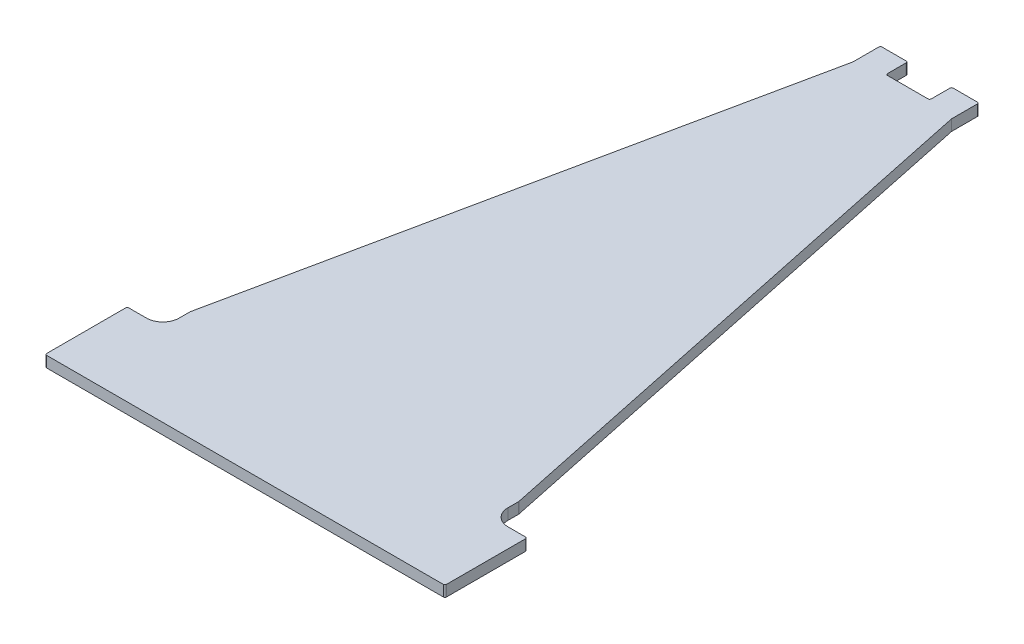
SolidWorks part; units mm, degrees
ref_plane "Front Plane" through (0, 0, 0) normal (0, 0, 1) x (1, 0, 0)
ref_plane "Top Plane" through (0, 0, 0) normal (0, 1, 0) x (1, 0, 0)
ref_plane "Right Plane" through (0, 0, 0) normal (1, 0, 0) x (0, 0, -1)
sketch "Sketch1" plane through (0, 0, 0) normal (0, 1, 0) x (1, 0, 0)
  line L0 (0, 0) -> (0, 1.5)
  line L1 (0, 1.5) -> (0.65, 1.5)
  line L2 (0.65, 1.5) -> (0.65, 2)
  line L3 (0.65, 2) -> (2.75, 12)
  line L4 (2.75, 12) -> (2.75, 12.5)
  line L5 (2.75, 12.5) -> (3.25, 12.5)
  line L6 (3.25, 12.5) -> (3.25, 12.1)
  line L7 (3.25, 12.1) -> (4.05, 12.1)
  line L8 (4.05, 12.1) -> (4.05, 12.5)
  line L9 (4.05, 12.5) -> (4.55, 12.5)
  line L10 (4.55, 12.5) -> (4.55, 12)
  line L11 (4.55, 12) -> (6.65, 2)
  line L12 (6.65, 2) -> (6.65, 1.5)
  line L13 (6.65, 1.5) -> (7.3, 1.5)
  line L14 (7.3, 1.5) -> (7.3, 0)
  line L19 (7.3, 0) -> (0, 0)
  point P3 (3.65, 12.1)
  point P18 (0.0213, 0)
  point P19 (7.2998, 0)
  point P27 (3.65, 0)
  dimension "D1" = 6
  dimension "D2" = 10
  dimension "D3" = 1.5
  dimension "D4" = 0.65
  dimension "D5" = 0.65
  dimension "D7" = 0.5
  dimension "D8" = 0.4
  dimension "D9" = 0.5
  dimension "D10" = 0.5
  dimension "D11" = 1.8
extrude "Boss-Extrude1" add sketch "Sketch1" along normal blind 0.2
fillet "Fillet1" radius 0.3 2 edges at (0.65, 0.1, -1.5) (6.65, 0.1, -1.5)
fillet "Fillet2" radius 0.03 14 edges at (7.3, 0.1, -1.5) (6.65, 0.1, -2) (4.55, 0.1, -12) (4.55, 0.1, -12.5) (4.05, 0.1, -12.5) (4.05, 0.1, -12.1) (3.25, 0.1, -12.1) (3.25, 0.1, -12.5) (2.75, 0.1, -12.5) (2.75, 0.1, -12) (0.65, 0.1, -2) (0, 0.1, -1.5) (7.3, 0.1, 0) (0, 0.1, 0)
